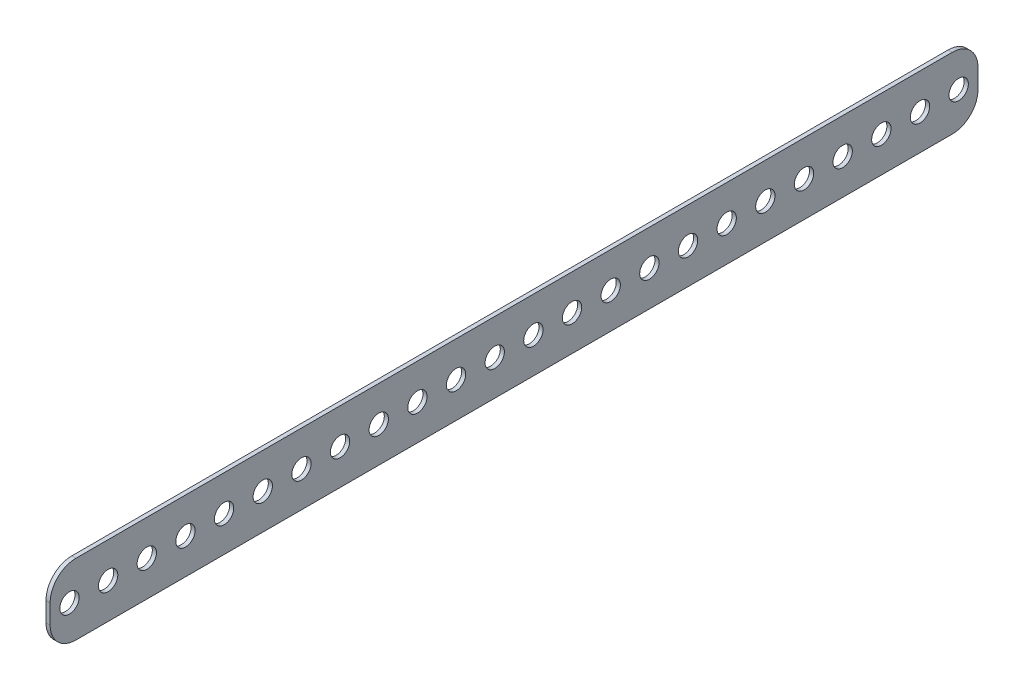
SolidWorks part; units mm, degrees
ref_plane "Front Plane" through (0, 0, 0) normal (0, 0, 1) x (1, 0, 0)
ref_plane "Top Plane" through (0, 0, 0) normal (0, 1, 0) x (1, 0, 0)
ref_plane "Right Plane" through (0, 0, 0) normal (1, 0, 0) x (0, 0, -1)
sketch "Sketch1" plane through (0, 0, 0) normal (0, 0, 1) x (1, 0, 0)
  line L1 (2.032, 0) -> (0, 0)
  line L2 (2.032, 0) -> (2.032, 34.925)
  line L3 (2.032, 34.925) -> (0, 34.925)
  line L4 (0, 0) -> (0, 34.925)
  dimension "D2" = 2.032
  dimension "D1" = 34.925
extrude "Boss-Extrude1" add sketch "Sketch1" along normal mid plane 457.2
sketch "Sketch2" plane through (0, 0, 0) normal (-1, 0, 0) x (0, 0, 1)
  line L0 (219.075, 17.4625) -> (200.025, 17.4625) construction
  line L1 (219.075, 17.4625) -> (228.6, 17.4625) construction
  line L2 (228.6, 0) -> (228.6, 34.925) construction
  circle A0 centre (219.075, 17.4625) radius 4.7625
  dimension "D1" = 9.525
  dimension "D2" = 19.05
  dimension "D3" = 9.525
extrude "Cut-Extrude1" cut sketch "Sketch2" against normal up to next
pattern_linear "LPattern1" count 24 spacing 19.05 along (0, 0, -1) of "Cut-Extrude1"
sketch "Sketch3" plane through (0, 0, 0) normal (1, 0, 0) x (0, 0, -1)
  line L0 (-228.6, 0) -> (-228.6, 34.925) construction
  point P0 (-19.05, 16.9798)
  dimension "D1" = 209.55
ref_plane "Plane1" through (0, 0, 19.05) normal (0, 0, 1) x (1, 0, 0)
sketch "Sketch4" plane through (0, 0, 19.05) normal (0, 0, 1) x (1, 0, 0)
  line L4 (0, 34.925) -> (0, 0)
  line L5 (2.032, 34.925) -> (0, 34.925)
  line L6 (2.032, 0) -> (2.032, 34.925)
  line L7 (0, 0) -> (2.032, 0)
  line L8 (0, 34.925) -> (0, 0)
  line L9 (2.032, 34.925) -> (0, 34.925)
  line L10 (2.032, 0) -> (2.032, 34.925)
  line L11 (0, 0) -> (2.032, 0)
  dimension "D1" = 0
fillet "Fillet1" radius 12.7 4 edges at (1.016, 34.925, -228.6) (1.016, 0, -228.6) (1.016, 0, 228.6) (1.016, 34.925, 228.6)
equation "\"D3@Sketch2\" = \"D2@Sketch2\" / 2"
equation "\"D3@LPattern1\" = \"D2@Sketch2\""
equation "\"D1@LPattern1\" = \"D1@Boss-Extrude1\" / \"D2@Sketch2\""
